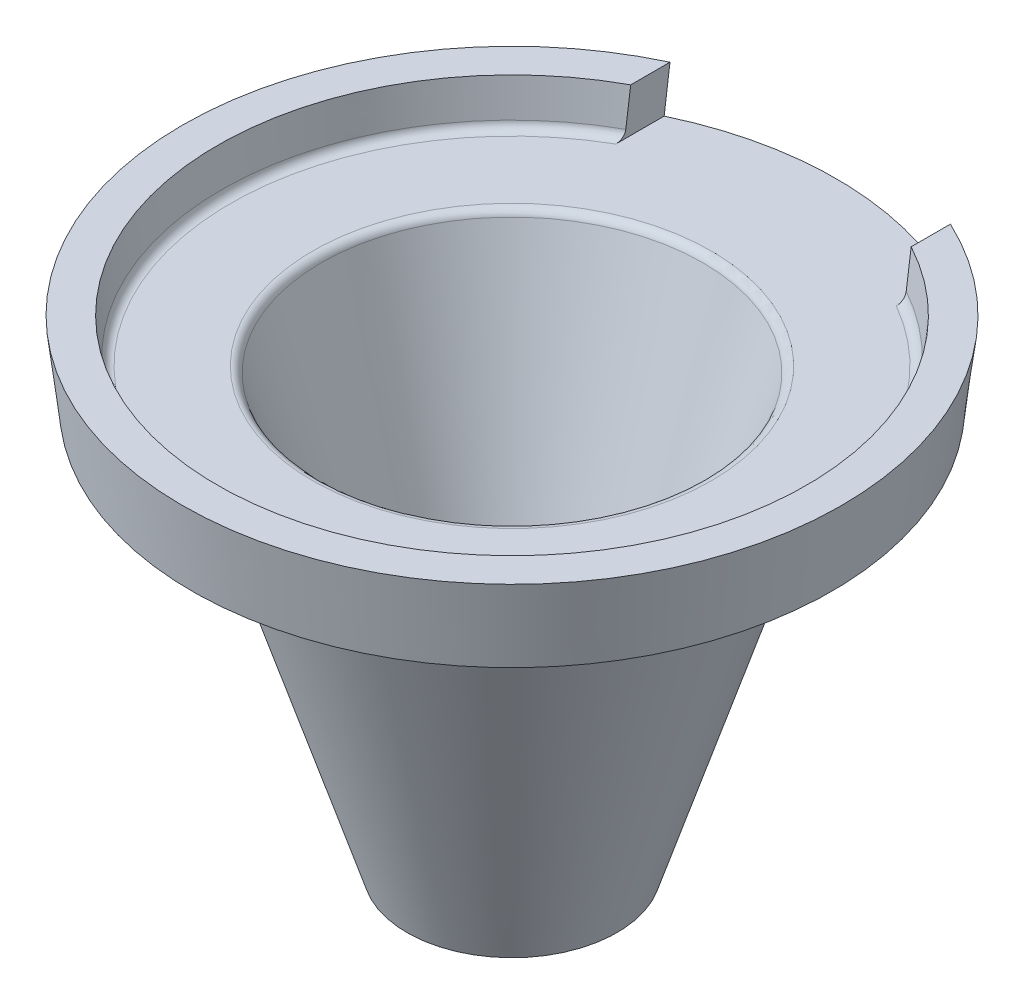
SolidWorks part; units mm, degrees
ref_plane "Front Plane" through (0, 0, 0) normal (0, 0, 1) x (1, 0, 0)
ref_plane "Top Plane" through (0, 0, 0) normal (0, 1, 0) x (1, 0, 0)
ref_plane "Right Plane" through (0, 0, 0) normal (1, 0, 0) x (0, 0, -1)
sketch "Sketch1" plane through (0, 0, 0) normal (0, 0, 1) x (1, 0, 0)
  line L0 (-6, 0) -> (-12, 0)
  line L1 (-12, 0) -> (-28, 50)
  line L2 (-28, 50) -> (-22, 50)
  line L3 (-22, 50) -> (-6, 0)
  line L4 (-28, 50) -> (0, 50) construction
  line L5 (0, 50) -> (0, 0) construction
  line L6 (0, 0) -> (-12, 0) construction
  line L7 (-37, 50) -> (-36.5209, 46)
  line L8 (-37, 50) -> (-22, 50)
  line L10 (-36.5209, 46) -> (-22, 46)
  line L11 (-22, 50) -> (-22, 46)
  line L12 (-37, 50) -> (-33, 50)
  line L13 (-33, 50) -> (-33.5988, 55)
  line L14 (-33.5988, 55) -> (-37.5988, 55)
  line L15 (-37.5988, 55) -> (-37, 50)
  line L16 (-33.5988, 55) -> (-38.15, 93) construction
  point P15 (-40.9161, 56.6575)
  point P16 (0, 0)
  point P17 (-38.15, 54.5858)
  point P18 (-38.15, 61.5489)
  point P19 (0, 0)
  dimension "D1" = 6
  dimension "D2" = 28
  dimension "D3" = 12
  dimension "D4" = 4
  dimension "50" = 50
  dimension "D5" = 9
  dimension "D6" = 33
  dimension "D7" = 38.15
  dimension "D8" = 43
  dimension "D9" = 5
revolve "Revolve1" add sketch "Sketch1" angle 360 about L5
sketch "Sketch2" plane through (0, 0, 0) normal (0, 0, 1) x (1, 0, 0)
  line L0 (37.5988, 55) -> (-37.5988, 55) construction
  line L1 (-16, 55) -> (16, 55)
  line L2 (-16, 55) -> (-16, 50)
  line L3 (-16, 50) -> (16, 50)
  line L4 (16, 55) -> (16, 50)
  line L6 (0, 55) -> (0, 0) construction
  line L7 (22, 50) -> (-22, 50) construction
  point P12 (0, 55)
  dimension "D1" = 32
extrude "Cut-Extrude2" cut sketch "Sketch2" against normal through all
fillet "Fillet1" radius 1 1 edges at (0, 50, 33)
fillet "Fillet2" radius 1 1 edges at (-22, 50, 0)
